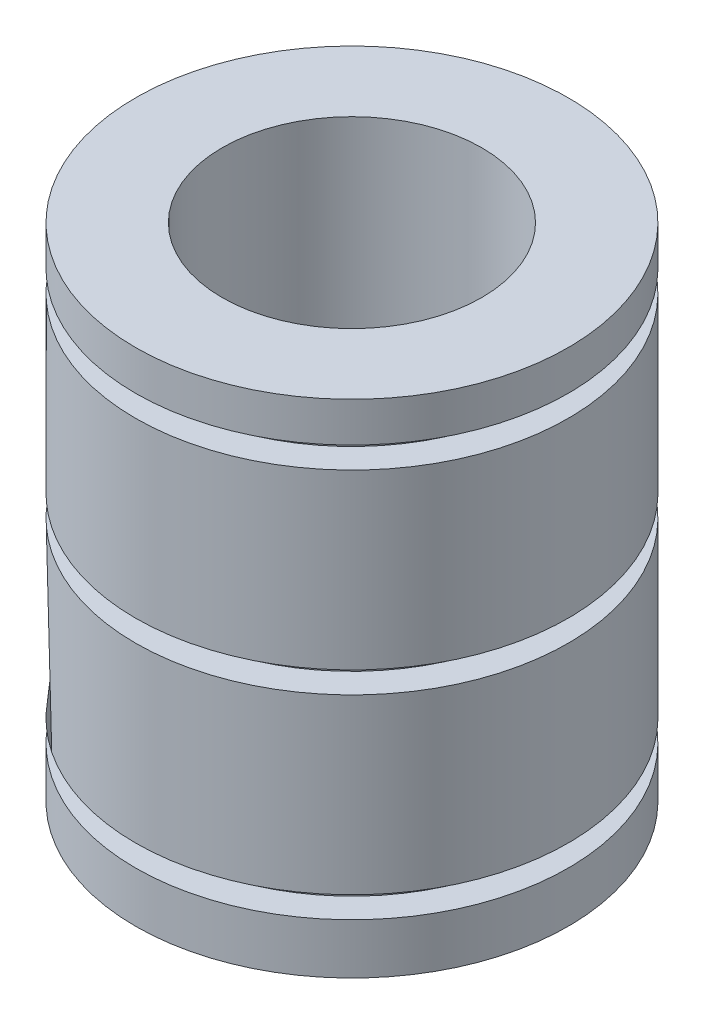
SolidWorks part; units mm, degrees
ref_plane "Front Plane" through (0, 0, 0) normal (0, 0, 1) x (1, 0, 0)
ref_plane "Top Plane" through (0, 0, 0) normal (0, 1, 0) x (1, 0, 0)
ref_plane "Right Plane" through (0, 0, 0) normal (1, 0, 0) x (0, 0, -1)
sketch "Sketch1" plane through (0, 0, 0) normal (0, 1, 0) x (1, 0, 0)
  circle A0 centre (0, 0) radius 15
  dimension "D1" = 30
extrude "Boss-Extrude1" add sketch "Sketch1" along normal blind 3.5
sketch "Sketch3" plane through (0, 3.5, 0) normal (0, 1, 0) x (1, 0, 0)
  circle A0 centre (0, 0) radius 13
  dimension "D1" = 26
extrude "Boss-Extrude2" add sketch "Sketch3" along normal blind 1.5
sketch "Sketch4" plane through (0, 5, 0) normal (0, 1, 0) x (1, 0, 0)
  circle A0 centre (0, 0) radius 15
  dimension "D1" = 30
extrude "Boss-Extrude3" add sketch "Sketch4" along normal blind 12
sketch "Sketch5" plane through (0, 17, 0) normal (0, 1, 0) x (1, 0, 0)
  circle A0 centre (0, 0) radius 13
  dimension "D1" = 26
extrude "Boss-Extrude4" add sketch "Sketch5" along normal blind 1.5
sketch "Sketch6" plane through (0, 18.5, 0) normal (0, 1, 0) x (1, 0, 0)
  circle A0 centre (0, 0) radius 15
  circle A1 centre (0, 0) radius 15 construction
  dimension "D1" = 0
extrude "Boss-Extrude5" add sketch "Sketch6" along normal blind 12
sketch "Sketch7" plane through (0, 30.5, 0) normal (0, 1, 0) x (1, 0, 0)
  circle A0 centre (0, 0) radius 13
  dimension "D1" = 26
extrude "Boss-Extrude6" add sketch "Sketch7" along normal blind 1.5
sketch "Sketch8" plane through (0, 32, 0) normal (0, 1, 0) x (1, 0, 0)
  circle A0 centre (0, 0) radius 15
  circle A1 centre (0, 0) radius 15 construction
  dimension "D1" = 0
extrude "Boss-Extrude7" add sketch "Sketch8" along normal blind 2.75
sketch "Sketch11" plane through (0, 34.75, 0) normal (0, 1, 0) x (1, 0, 0)
  circle A0 centre (0, 0) radius 6
extrude "Boss-Extrude8" [suppressed] add sketch "Sketch11" along normal blind 5
sketch "Sketch9" plane through (0, 0, 0) normal (0, 1, 0) x (1, 0, 0)
  circle A0 centre (0, 0) radius 9
  dimension "D1" = 18
extrude "Cut-Extrude1" cut sketch "Sketch9" against normal through all both and the other way through all
ref_plane "Plane2" through (0, 5, 0) normal (0, 1, 0) x (1, 0, 0)
sketch "Sketch12" plane through (0, 5, 0) normal (0, 1, 0) x (1, 0, 0)
  circle A0 centre (0, 0) radius 9
  circle A1 centre (0, 0) radius 9 construction
  dimension "D1" = 0
extrude "Boss-Extrude9" add sketch "Sketch12" along normal blind 2
sketch "Sketch13" plane through (0, 5, 0) normal (0, 1, 0) x (1, 0, 0)
  line L0 (0, -16.5) -> (0, 16.5) construction
  line L1 (-16.5, 0) -> (16.5, 0) construction
  circle A0 centre (0, 0) radius 1.5
  circle A1 centre (0, 7) radius 1.5
  circle A2 centre (0, -7) radius 1.5
  circle A3 centre (7, 0) radius 1.5
  circle A4 centre (-7, 0) radius 1.5
  dimension "D1" = 3
  dimension "D2" = 14
  dimension "D3" = 7
  dimension "D4" = 14
  dimension "D5" = 7
extrude "Cut-Extrude3" cut sketch "Sketch13" against normal through all both and the other way through all
ref_plane "Plane3" through (-15, 0, 0) normal (1, 0, 0) x (0, 0, -1)
sketch "Sketch14" plane through (-15, 0, 0) normal (1, 0, 0) x (0, 0, -1)
  line L0 (15, 34.75) -> (-15, 34.75) construction
  line L1 (-2.5, 34.75) -> (2.5, 34.75)
  line L2 (-2.5, 34.75) -> (-2.5, 0)
  line L3 (-2.5, 0) -> (2.5, 0)
  line L4 (2.5, 34.75) -> (2.5, 0)
  line L5 (16.5, 0) -> (-16.5, 0) construction
  line L6 (0, 16.5) -> (0, -16.5) construction
  dimension "D1" = 5
  dimension "D2" = 2.5
extrude "Boss-Extrude10" add sketch "Sketch14" along normal blind 1
sketch "Sketch15" plane through (0, 34.75, 0) normal (0, 1, 0) x (1, 0, 0)
  circle A0 centre (0, 0) radius 15
  circle A1 centre (0, 0) radius 15.4087
  arc A2 (-14.7902, -2.5) -> (-14.7902, 2.5) centre (0, 0) ccw construction
  dimension "D1" = 0
extrude "Cut-Extrude4" cut sketch "Sketch15" against normal through all both and the other way through all
